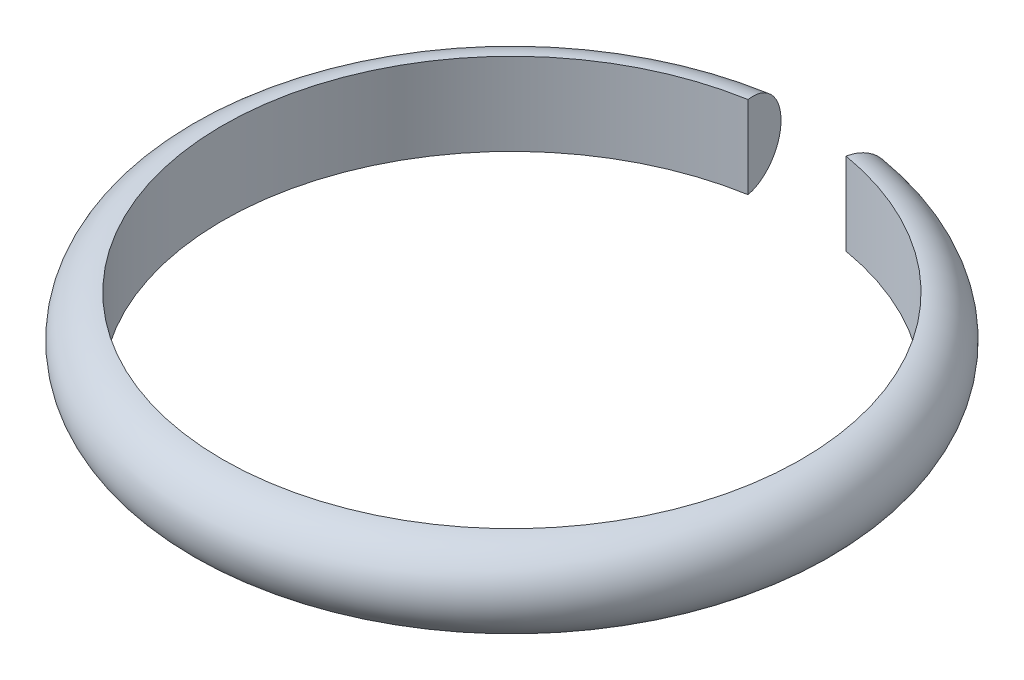
SolidWorks part; units mm, degrees
material "ABS PC"
ref_plane "Plan de face" through (0, 0, 0) normal (0, 0, 1) x (1, 0, 0)
ref_plane "Plan de dessus" through (0, 0, 0) normal (0, 1, 0) x (1, 0, 0)
ref_plane "Plan de droite" through (0, 0, 0) normal (1, 0, 0) x (0, 0, -1)
sketch "Esquisse1" plane through (0, 0, 0) normal (0, 1, 0) x (1, 0, 0)
  line L0 (-5.927, 34.4945) -> (5.927, 34.4945) construction
  arc A0 (-5.927, 34.4945) -> (5.927, 34.4945) centre (0, 0) ccw
  dimension "D1" = 35
  dimension "D2" = 208
  dimension "D3" = 11.8541
sweep "Balayage1" add path "Esquisse1" circular profile diameter 10 parameters "D3"=10
sketch "Esquisse10" plane through (0, 0, 0) normal (0, 1, 0) x (1, 0, 0)
  circle A0 centre (0, 0) radius 35.1
  dimension "D1" = 70.2
extrude "Enlèv. mat.-Extru.1" cut sketch "Esquisse10" against normal through all both and the other way through all
